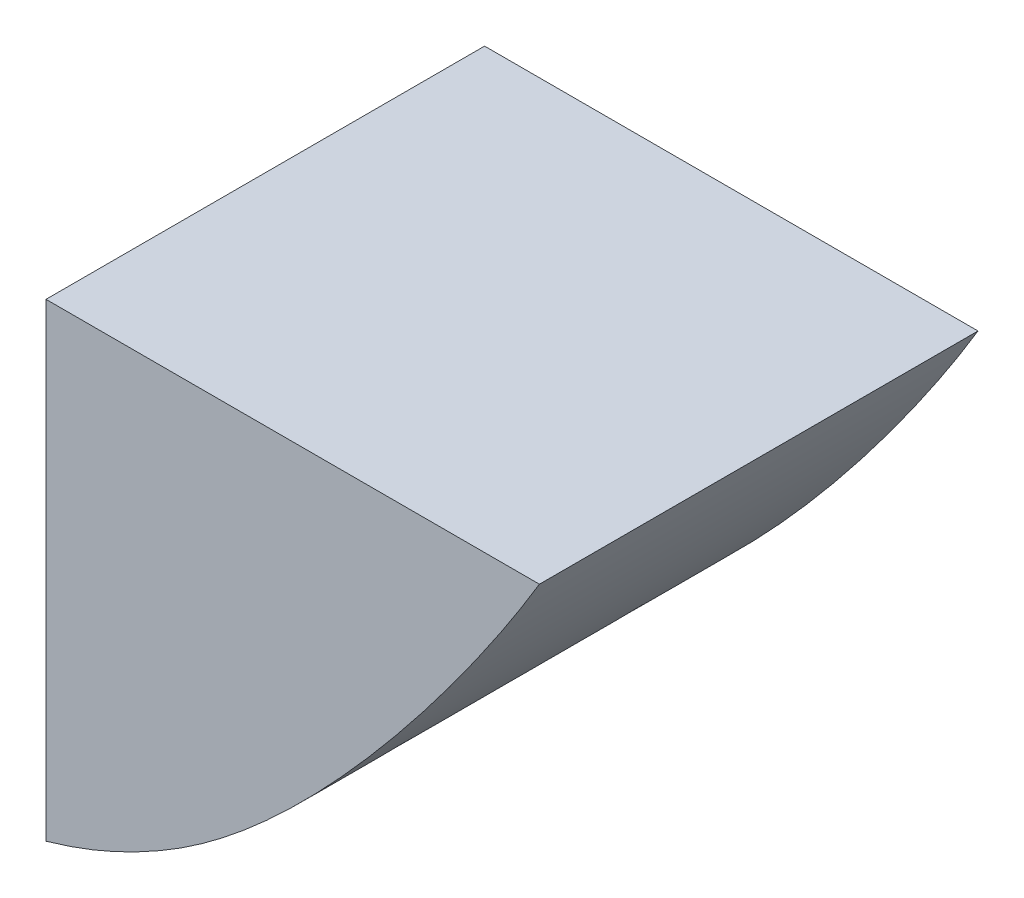
SolidWorks part; units mm, degrees
ref_plane "Front Plane" through (0, 0, 0) normal (0, 0, 1) x (1, 0, 0)
ref_plane "Top Plane" through (0, 0, 0) normal (0, 1, 0) x (1, 0, 0)
ref_plane "Right Plane" through (0, 0, 0) normal (1, 0, 0) x (0, 0, -1)
ref_plane "plane:profile" through (0, 0, 0) normal (0, 0, 1) x (1, 0, 0)
sketch "profile:rational" plane through (0, 0, 0) normal (0, 0, 1) x (1, 0, 0)
  line L0 (12, 9) -> (0, 9)
  line L1 (0, 9) -> (0, 0)
  spline S0 degree 3 poles (0, 0) (2, 0) (5, 1) (9, 4) (12, 9) knots 0 0 0 0 0.4 1 1 1 1 weights 1 0.8 1.3 0.9 1.1
extrude "feature:prism" add sketch "profile:rational" along normal blind 8 separate body
sketch "profile:cut" plane through (0, 0, 0) normal (0, 0, 1) x (1, 0, 0)
  line L0 (-2, -2) -> (3, -2)
  line L1 (3, -2) -> (3, 11)
  line L2 (3, 11) -> (-2, 11)
  line L3 (-2, 11) -> (-2, -2)
extrude "feature:trim" cut sketch "profile:cut" along normal through all
